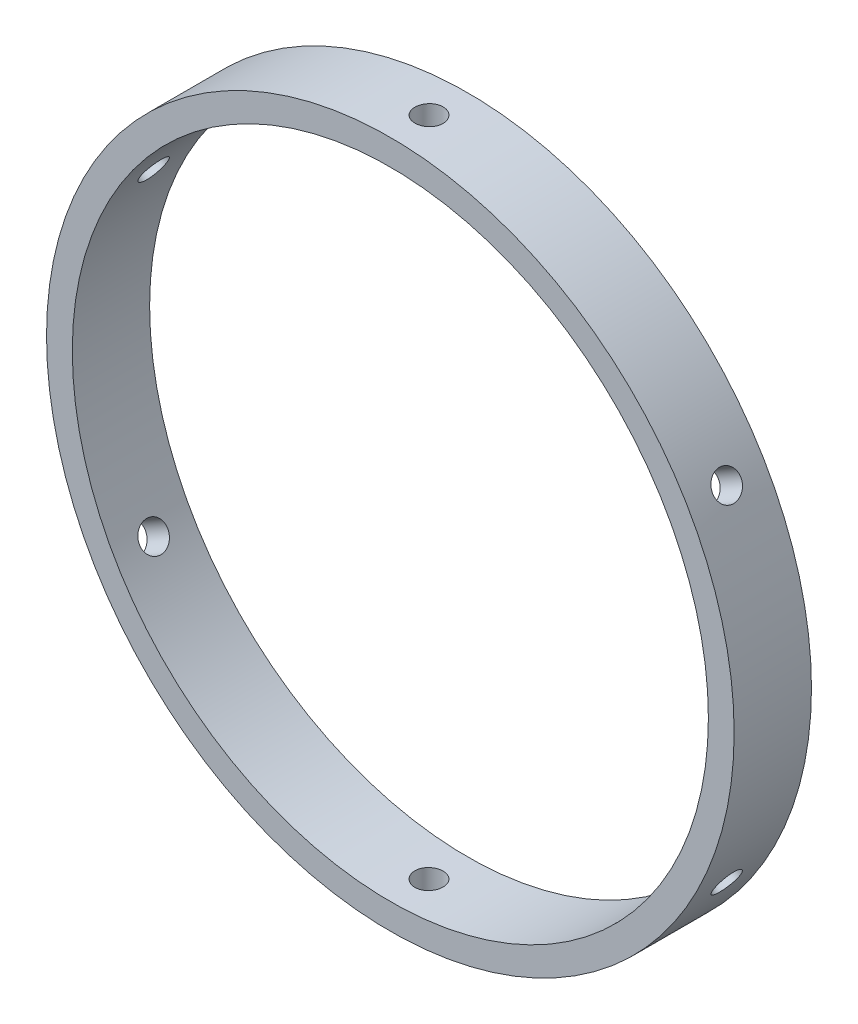
SolidWorks part; units mm, degrees
ref_plane "Front Plane" through (0, 0, 0) normal (0, 0, 1) x (1, 0, 0)
ref_plane "Top Plane" through (0, 0, 0) normal (0, 1, 0) x (1, 0, 0)
ref_plane "Right Plane" through (0, 0, 0) normal (1, 0, 0) x (0, 0, -1)
sketch "Sketch1" plane through (0, 0, 0) normal (0, 0, 1) x (1, 0, 0)
  circle A0 centre (0, 0) radius 78.359
  circle A1 centre (0, 0) radius 84.709
  dimension "D1" = 156.718
  dimension "D2" = 169.418
extrude "Boss-Extrude1" add sketch "Sketch1" along normal blind 19.05
sketch "Sketch2" plane through (0, 0, 0) normal (0, 1, 0) x (1, 0, 0)
  line L0 (78.359, 0) -> (-78.359, 0) construction
  line L1 (0, -2.0807) -> (0, -15.8358) construction
  circle A0 centre (0, -9.525) radius 3.4782
  dimension "D1" = 9.525
extrude "Cut-Extrude1" cut sketch "Sketch2" against normal through all
ref_axis "Axis1" through (0, 0, 2.0807) along (0, 0, 1)
pattern_circular "CirPattern1" count 6 over 360 about axis through (0, 0, 2.0807) along (0, 0, 1) of "Cut-Extrude1"
